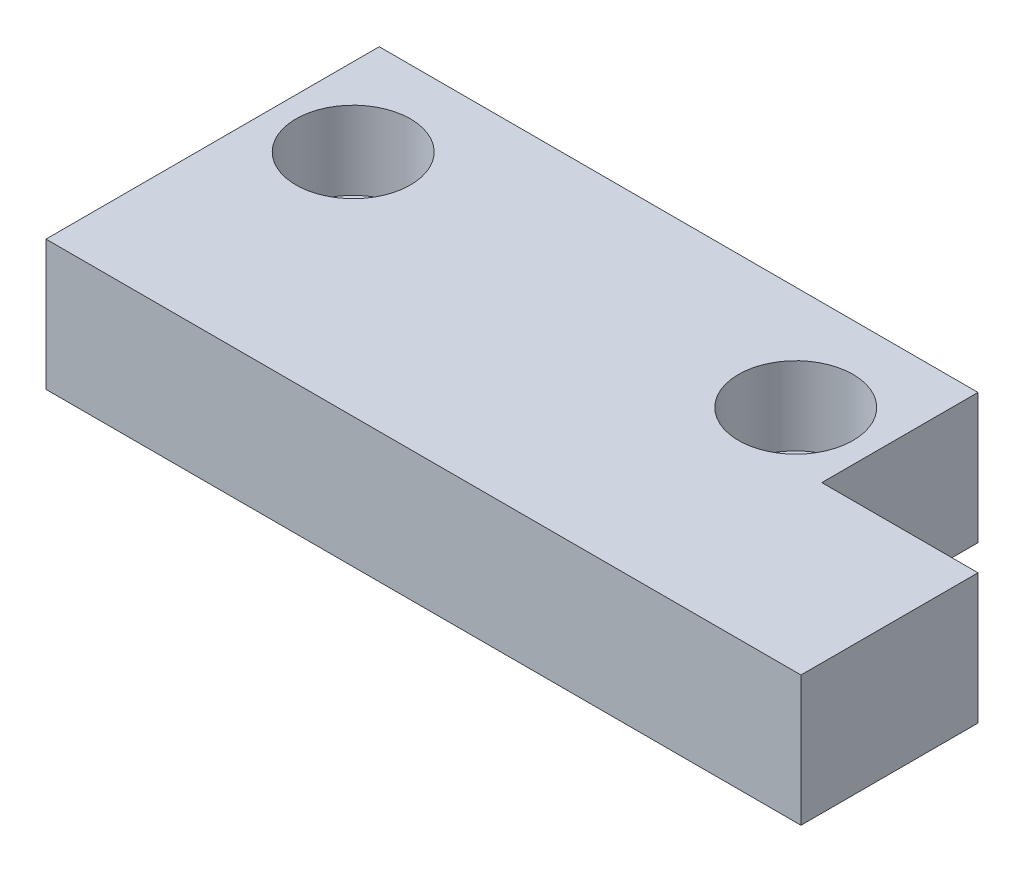
SolidWorks part; units mm, degrees
ref_plane "前基準面" through (0, 0, 0) normal (0, 0, 1) x (1, 0, 0)
ref_plane "上基準面" through (0, 0, 0) normal (0, 1, 0) x (1, 0, 0)
ref_plane "右基準面" through (0, 0, 0) normal (1, 0, 0) x (0, 0, -1)
sketch "草圖1" plane through (0, 0, 0) normal (0, 1, 0) x (1, 0, 0)
  line L1 (0, 0) -> (35, 0)
  line L2 (0, 0) -> (0, 20)
  line L3 (0, 20) -> (35, 20)
  line L4 (35, 0) -> (35, 20)
  dimension "D1" = 35
  dimension "D2" = 20
extrude "填料-伸長1" add sketch "草圖1" along normal blind 5
sketch "草圖3" plane through (0, 0, 0) normal (0, 1, 0) x (1, 0, 0)
  line L1 (6, 0) -> (35, 0)
  line L2 (6, 0) -> (6, 7.2)
  line L3 (6, 7.2) -> (35, 7.2)
  line L4 (35, 0) -> (35, 7.2)
  dimension "D1" = 29
  dimension "D2" = 7.2
extrude "除料-伸長4" cut sketch "草圖3" along normal blind 5
sketch "草圖4" plane through (0, 0, 0) normal (0, 1, 0) x (1, 0, 0)
  line L1 (35, 20) -> (29, 20)
  line L2 (35, 20) -> (35, 14)
  line L3 (35, 14) -> (29, 14)
  line L4 (29, 20) -> (29, 14)
  dimension "D1" = 6
  dimension "D2" = 6
extrude "除料-伸長5" cut sketch "草圖4" along normal blind 5
sketch "草圖5" plane through (0, 0, 0) normal (0, 1, 0) x (1, 0, 0)
  circle A0 centre (3, 16) radius 1.2
  circle A1 centre (3, 4) radius 1.2
  circle A2 centre (9, 16) radius 1.2
  circle A4 centre (26, 16) radius 1.2
extrude "除料-伸長6" cut sketch "草圖5" along normal through all
sketch "草圖7" plane through (0, 0, 0) normal (0, 1, 0) x (1, 0, 0)
  circle A0 centre (9, 16) radius 2.2
  circle A1 centre (26, 16) radius 2.2
extrude "除料-伸長8" cut sketch "草圖7" against normal blind 3 from surface at 5 starting at face at (9, 5, -14.8)
sketch "草圖8" plane through (0, 5, 0) normal (0, 1, 0) x (1, 0, 0)
  line L0 (29, 20) -> (0, 20) construction
  line L1 (0, 0) -> (6, 0)
  line L2 (0, 0) -> (0, 20)
  line L3 (0, 20) -> (6, 20)
  line L4 (6, 0) -> (6, 20)
  dimension "D1" = 6
extrude "除料-伸長9" cut sketch "草圖8" against normal blind 10
